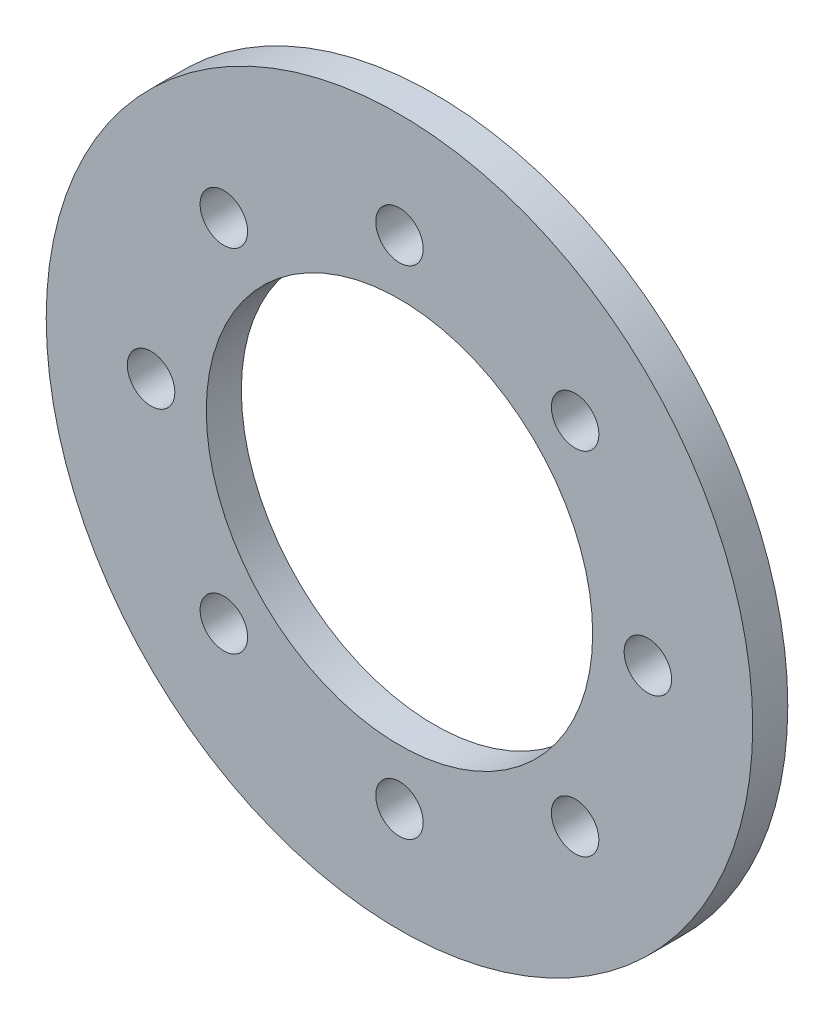
SolidWorks part; units mm, degrees
ref_plane "Front Plane" through (0, 0, 0) normal (1, 0, 0) x (0, 1, 0)
ref_plane "Top Plane" through (0, 0, 0) normal (0, 0, 1) x (0, 1, 0)
ref_plane "Right Plane" through (0, 0, 0) normal (0, 1, 0) x (-1, 0, 0)
sketch "Sketch1" plane through (0, 0, 0) normal (0, 0, 1) x (0, 1, 0)
  circle A0 centre (0, 0) radius 32
  circle A1 centre (0, 0) radius 17.5
  circle A2 centre (0, 22.5) radius 2.15
  circle A3 centre (15.9099, 15.9099) radius 2.15
  circle A4 centre (22.5, 0) radius 2.15
  circle A5 centre (15.9099, -15.9099) radius 2.15
  circle A6 centre (0, -22.5) radius 2.15
  circle A7 centre (-15.9099, -15.9099) radius 2.15
  circle A8 centre (-22.5, 0) radius 2.15
  circle A9 centre (-15.9099, 15.9099) radius 2.15
  point P7 (18.0672, 18.3949)
  point P8 (0, 0)
  point P22 (0, 0)
  dimension "D1" = 64
  dimension "D2" = 35
  dimension "D3" = 4.3
  dimension "D4" = 22.5
  dimension "D5" = 8
extrude "Boss-Extrude1" add sketch "Sketch1" along normal mid plane 3.175
